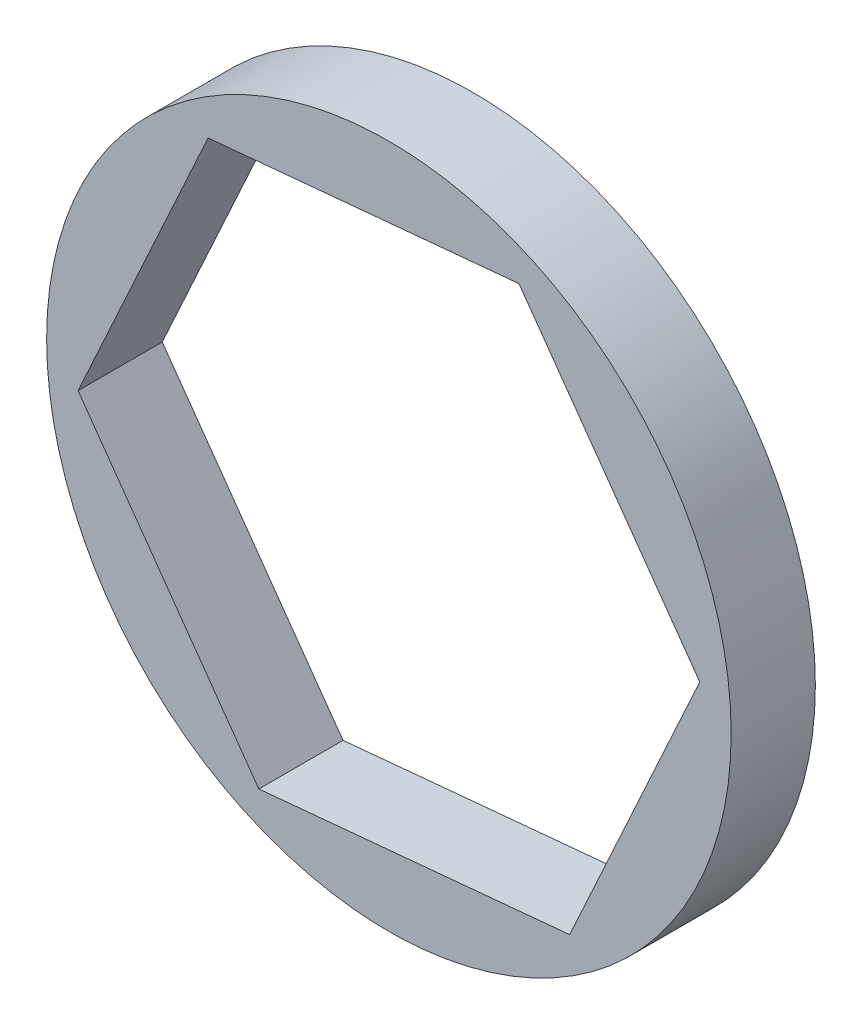
SolidWorks part; units mm, degrees
material "ABS"
ref_plane "Front Plane" through (0, 0, 0) normal (0, 0, 1) x (1, 0, 0)
ref_plane "Top Plane" through (0, 0, 0) normal (0, 1, 0) x (1, 0, 0)
ref_plane "Right Plane" through (0, 0, 0) normal (1, 0, 0) x (0, 0, -1)
sketch "Sketch1" plane through (0, 0, 0) normal (0, 0, 1) x (1, 0, 0)
  line L1 (-3.3539, 4.7228) -> (-5.767, -0.5431)
  line L2 (-5.767, -0.5431) -> (-2.4131, -5.266)
  line L3 (-2.4131, -5.266) -> (3.3539, -4.7228)
  line L4 (3.3539, -4.7228) -> (5.767, 0.5431)
  line L5 (5.767, 0.5431) -> (2.4131, 5.266)
  line L6 (2.4131, 5.266) -> (-3.3539, 4.7228)
  circle A0 centre (0, 0) radius 5.0165 construction
  circle A1 centre (0, 0) radius 6.35
  dimension "D2" = 12.7
  dimension "D1" = 10.033
extrude "Boss-Extrude1" add sketch "Sketch1" along normal blind 1.5621
